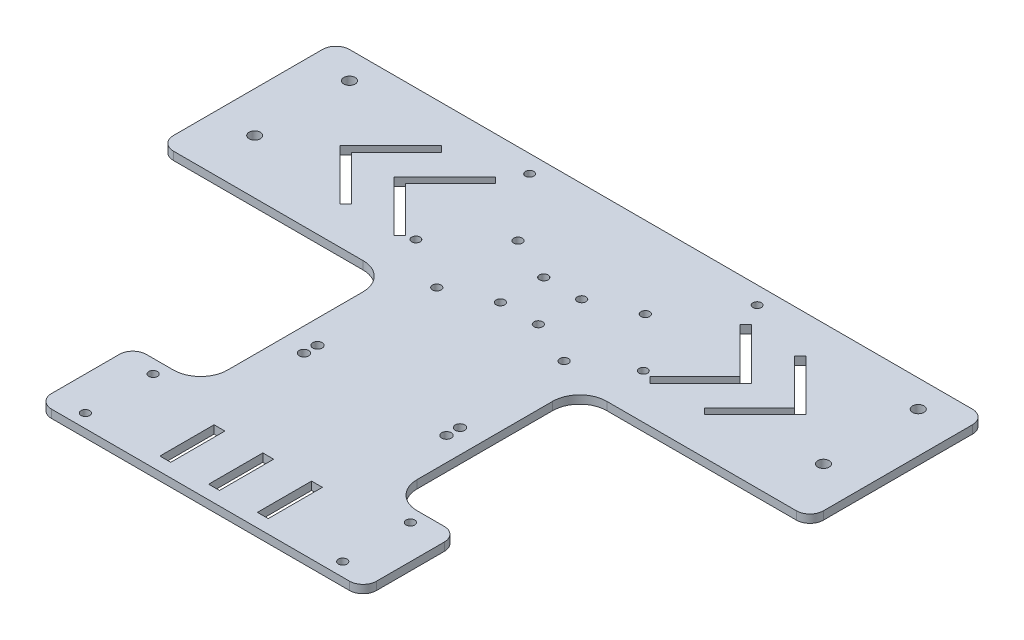
SolidWorks part; units mm, degrees
material "Thornel Mat VMA"
ref_plane "前视基准面" through (0, 0, 0) normal (0, 0, 1) x (1, 0, 0)
ref_plane "上视基准面" through (0, 0, 0) normal (0, 1, 0) x (1, 0, 0)
ref_plane "右视基准面" through (0, 0, 0) normal (1, 0, 0) x (0, 0, -1)
sketch "草图1" plane through (0, 0, 0) normal (0, 1, 0) x (1, 0, 0)
  line L0 (-105, 32.5) -> (-105, -32.5) construction
  line L1 (-120, -32.5) -> (120, -32.5)
  line L2 (-120, -32.5) -> (-120, 32.5)
  line L3 (-120, 32.5) -> (120, 32.5)
  line L4 (120, -32.5) -> (120, 32.5)
  line L5 (-120, -32.5) -> (120, 32.5) construction
  line L6 (-120, 32.5) -> (120, -32.5) construction
  line L7 (0, 32.5) -> (0, -32.5) construction
  line L8 (0, -82.5) -> (0, -32.5) construction
  line L9 (-60, -32.5) -> (20, -32.5)
  circle A0 centre (-105, 22.5) radius 2.1
  circle A1 centre (-105, -12.5) radius 2.1
  circle A2 centre (105, -12.5) radius 2.1
  circle A3 centre (105, 22.5) radius 2.1
  point P0 (0, 0)
  dimension "D4" = 20
  dimension "D5" = 35
  dimension "D1" = 65
  dimension "D2" = 240
  dimension "D3" = 15
extrude "凸台-拉伸1" add sketch "草图1" along normal blind 3
sketch "草图3" plane through (0, 3, 0) normal (0, 1, 0) x (1, 0, 0)
  line L0 (0.7261, -44.1829) -> (0.7261, -109.1829) construction
  line L2 (-120, -32.5) -> (120, -32.5) construction
  line L3 (-40, -12.5) -> (40, -12.5) construction
  circle A0 centre (-22.7739, 2.5) radius 1.6
  circle A1 centre (24.2261, 2.5) radius 1.6
  circle A2 centre (24.2261, -27.5) radius 1.6
  circle A3 centre (-22.7739, -27.5) radius 1.6
  circle A4 centre (-6.2739, -4.5) radius 1.6
  circle A5 centre (7.7261, -4.5) radius 1.6
  circle A6 centre (7.7261, -20.5) radius 1.6
  circle A7 centre (-6.2739, -20.5) radius 1.6
  dimension "D1" = 3.2
  dimension "D2" = 47
  dimension "D3" = 30
  dimension "D4" = 14
  dimension "D5" = 16
  dimension "D6" = 5
extrude "切除-拉伸1" cut sketch "草图3" against normal through all
sketch "草图4" plane through (0, 0, 0) normal (0, 1, 0) x (1, 0, 0)
  line L0 (0, 32.5) -> (0, -113.7655) construction
  line L2 (-35, -32.5) -> (-35, -137.5)
  line L3 (-120, -32.5) -> (120, -32.5) construction
  line L4 (-35, -137.5) -> (35, -137.5)
  line L5 (35, -32.5) -> (35, -137.5)
  line L6 (-35, -32.5) -> (35, -32.5)
  line L7 (-35, -102.5) -> (-60, -102.5)
  line L8 (-60, -102.5) -> (-60, -137.5)
  line L9 (-60, -137.5) -> (-35, -137.5)
  line L10 (60, -102.5) -> (60, -137.5)
  line L11 (60, -137.5) -> (35, -137.5)
  line L12 (35, -102.5) -> (60, -102.5)
  point P9 (0, -137.5)
  dimension "D1" = 105
  dimension "D2" = 35
  dimension "D3" = 60
  dimension "D4" = 35
extrude "凸台-拉伸2" add sketch "草图4" along normal blind 3 contours L0 L6 L2 L4 | L6 L0 L4 L5 | L8 L9 L2 L7 | L12 L5 L11 L10
fillet "圆角1" radius 10 2 edges at (35, 1.5, 32.5) (-35, 1.5, 32.5)
sketch "草图5" plane through (0, 3, 0) normal (0, 1, 0) x (1, 0, 0)
  line L0 (0, 32.5) -> (0, -137.5) construction
  line L1 (-120, 32.5) -> (120, 32.5) construction
  line L2 (-2, -112.5) -> (2, -112.5)
  line L3 (-120, -132.5) -> (120, -132.5) construction
  line L4 (-120, -32.5) -> (-120, 32.5) construction
  line L5 (120, -32.5) -> (120, 32.5) construction
  line L6 (-20, -112.5) -> (-16, -112.5)
  line L7 (-60, -137.5) -> (60, -137.5) construction
  line L8 (-20, -112.5) -> (-20, -132.5)
  line L9 (-20, -132.5) -> (-16, -132.5)
  line L10 (-16, -112.5) -> (-16, -132.5)
  line L11 (-2, -112.5) -> (-2, -132.5)
  line L12 (2, -112.5) -> (2, -132.5)
  line L13 (-2, -132.5) -> (2, -132.5)
  line L14 (16, -112.5) -> (20, -112.5)
  line L15 (16, -112.5) -> (16, -132.5)
  line L16 (20, -112.5) -> (20, -132.5)
  line L17 (16, -132.5) -> (20, -132.5)
  circle A0 centre (-47.5, -132.5) radius 1.6
  circle A1 centre (47.5, -132.5) radius 1.6
  circle A2 centre (-47.5, -107.5) radius 1.6
  circle A3 centre (47.5, -107.5) radius 1.6
  point P25 (-18, -112.5)
  point P33 (18, -112.5)
  dimension "D2" = 3.2
  dimension "D3" = 95
  dimension "D1" = 5
  dimension "D5" = 20
  dimension "D6" = 16
  dimension "D7" = 4
  dimension "D9" = 36
  dimension "D4" = 2
  dimension "D8" = 3
extrude "切除-拉伸2" cut sketch "草图5" against normal through all
fillet "圆角2" radius 10 2 edges at (35, 1.5, 102.5) (-35, 1.5, 102.5)
sketch "草图7" plane through (0, 3, 0) normal (0, 1, 0) x (1, 0, 0)
  line L0 (-120, 0) -> (120, 0) construction
  line L1 (-120, -32.5) -> (-120, 32.5) construction
  line L2 (120, -32.5) -> (120, 32.5) construction
  line L3 (0, 32.5) -> (0, -32.5) construction
  line L4 (-120, 32.5) -> (120, 32.5) construction
  line L5 (-105, 22.5) -> (-105, -12.5) construction
  line L6 (-22.7739, 2.5) -> (-22.7739, -27.5) construction
  line L7 (-22.7739, 2.5) -> (-105, 2.5) construction
  line L8 (-63.887, 2.5) -> (-63.887, 0) construction
  line L9 (-63.887, 0) -> (-46.2093, 17.6777)
  line L10 (-83.887, 0) -> (-66.2093, 17.6777)
  line L11 (-63.887, 0) -> (-46.2093, -17.6777)
  line L12 (-83.887, 0) -> (-66.2093, -17.6777)
  line L13 (83.887, 0) -> (66.2093, -17.6777)
  line L14 (63.887, 0) -> (46.2093, -17.6777)
  line L15 (63.887, 0) -> (46.2093, 17.6777)
  line L16 (83.887, 0) -> (66.2093, 17.6777)
  dimension "D1" = 25
  dimension "D2" = 45
  dimension "D3" = 2
extrude "切除-拉伸-薄壁1" cut sketch "草图7" against normal through all thin thin type mid plane wall 3
sketch "草图8" plane through (0, 3, 0) normal (0, 1, 0) x (1, 0, 0)
  line L0 (-35, -42.5) -> (35, -42.5) construction
  line L1 (35, -92.5) -> (-35, -92.5) construction
  line L2 (0, -42.5) -> (0, -92.5) construction
  line L3 (-35, -70.5) -> (35, -70.5) construction
  line L6 (-120, -32.5) -> (-45, -32.5) construction
  circle A0 centre (-26.3163, -68) radius 1.75
  circle A1 centre (-26.3163, -73) radius 1.75
  circle A2 centre (26.3163, -73) radius 1.75
  circle A3 centre (26.3163, -68) radius 1.75
  point P24 (22.8506, -71.4342)
  dimension "D1" = 3.5
  dimension "D2" = 52.6327
  dimension "D3" = 38
extrude "切除-拉伸5" cut sketch "草图8" against normal through all
sketch "草图9" plane through (0, 3, 0) normal (0, 1, 0) x (1, 0, 0)
  line L0 (-105, 22.5) -> (-105, -12.5) construction
  line L1 (-105, -12.5) -> (105, -12.5) construction
  line L2 (-105, 5) -> (105, 5) construction
  line L3 (0, 26) -> (0, -16) construction
  line L4 (-42, -16) -> (42, -16) construction
  line L5 (-42, -16) -> (-42, 26) construction
  line L6 (-42, 26) -> (42, 26) construction
  line L7 (42, -16) -> (42, 26) construction
  line L8 (-42, -16) -> (42, 26) construction
  line L9 (-42, 26) -> (42, -16) construction
  circle A0 centre (-42, 26) radius 1.55
  circle A1 centre (-42, -16) radius 1.55
  circle A2 centre (42, -16) radius 1.55
  circle A3 centre (42, 26) radius 1.55
  point P8 (0, 5)
  dimension "D3" = 3.1
  dimension "D1" = 84
  dimension "D2" = 42
extrude "切除-拉伸6" cut sketch "草图9" against normal through all
fillet "圆角3" radius 5 8 edges at (-60, 1.5, 102.5) (-60, 1.5, 137.5) (60, 1.5, 102.5) (60, 1.5, 137.5) (120, 1.5, -32.5) (120, 1.5, 32.5) (-120, 1.5, 32.5) (-120, 1.5, -32.5)
